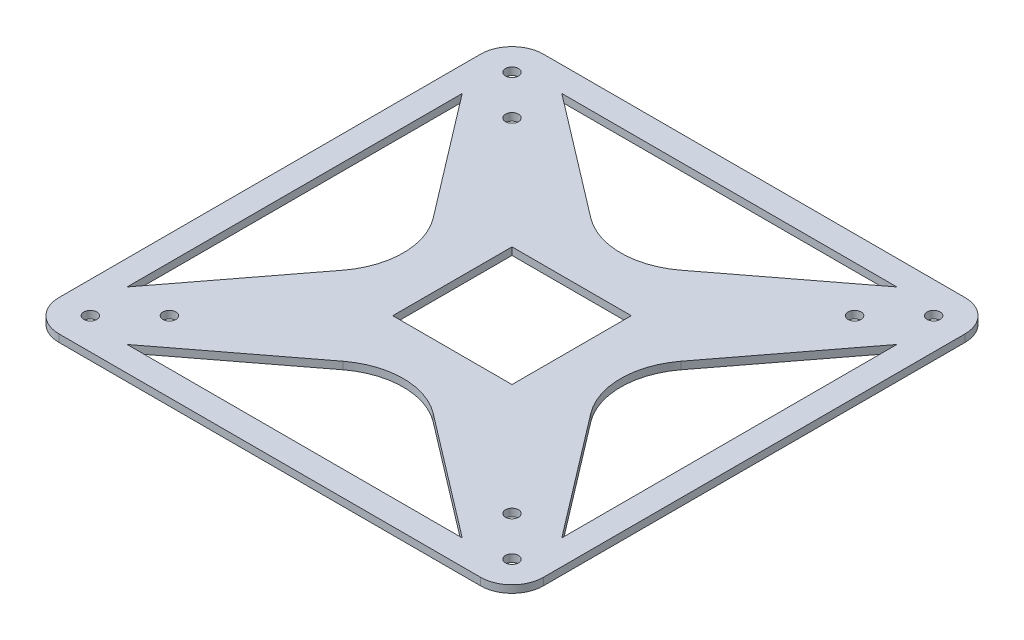
SolidWorks part; units mm, degrees
ref_plane "前视基准面" through (0, 0, 0) normal (0, 0, 1) x (1, 0, 0)
ref_plane "上视基准面" through (0, 0, 0) normal (0, 1, 0) x (1, 0, 0)
ref_plane "右视基准面" through (0, 0, 0) normal (1, 0, 0) x (0, 0, -1)
sketch "草图1" plane through (0, 0, 0) normal (0, 1, 0) x (1, 0, 0)
  line L0 (-12.1309, 33.2719) -> (-44.9616, 58.3185)
  line L5 (-55.3311, 55.3311) -> (-62.9289, 62.9289) construction
  line L6 (33.2719, 12.1309) -> (58.3185, 44.9616)
  line L7 (-33.2719, 12.1309) -> (-58.3185, 44.9616)
  line L8 (12.1309, 33.2719) -> (44.9616, 58.3185)
  line L9 (12.1309, -33.2719) -> (44.9616, -58.3185)
  line L10 (33.2719, -12.1309) -> (58.3185, -44.9616)
  line L11 (-33.2719, -12.1309) -> (-58.3185, -44.9616)
  line L12 (-12.1309, -33.2719) -> (-44.9616, -58.3185)
  line L13 (0, 0) -> (62.5305, 62.5305) construction
  line L14 (-44.9616, 58.3185) -> (44.9616, 58.3185)
  line L15 (-16, -16) -> (16, -16)
  line L16 (-16, -16) -> (-16, 16)
  line L17 (-16, 16) -> (16, 16)
  line L18 (16, -16) -> (16, 16)
  line L19 (-16, -16) -> (16, 16) construction
  line L20 (-16, 16) -> (16, -16) construction
  line L21 (-56.5685, 65) -> (56.5685, 65)
  line L22 (58.3185, 44.9616) -> (58.3185, -44.9616)
  line L23 (65, 56.5685) -> (65, -56.5685)
  line L24 (44.9616, -58.3185) -> (-44.9616, -58.3185)
  line L25 (56.5685, -65) -> (-56.5685, -65)
  line L26 (-58.3185, -44.9616) -> (-58.3185, 44.9616)
  line L27 (-65, -56.5685) -> (-65, 56.5685)
  line L28 (-12.1309, 26.5631) -> (-12.1309, 47.4181) construction
  line L29 (0, 29.1728) -> (0, 24.1728) construction
  circle A0 centre (-56.5685, 56.5685) radius 1.75
  arc A1 (-56.5685, 65) -> (-65, 56.5685) centre (-56.5685, 56.5685) ccw
  circle A2 centre (56.5685, 56.5685) radius 1.75
  arc A3 (65, 56.5685) -> (56.5685, 65) centre (56.5685, 56.5685) ccw
  circle A4 centre (56.5685, -56.5685) radius 1.75
  arc A5 (56.5685, -65) -> (65, -56.5685) centre (56.5685, -56.5685) ccw
  circle A6 centre (-56.5685, -56.5685) radius 1.75
  arc A7 (-65, -56.5685) -> (-56.5685, -65) centre (-56.5685, -56.5685) ccw
  circle A8 centre (45.9619, 45.9619) radius 1.75
  arc A13 (-33.2719, 12.1309) -> (-33.2719, -12.1309) centre (-49.1728, 0) cw
  arc A14 (-12.1309, -33.2719) -> (12.1309, -33.2719) centre (0, -49.1728) cw
  arc A15 (33.2719, -12.1309) -> (33.2719, 12.1309) centre (49.1728, 0) cw
  arc A16 (12.1309, 33.2719) -> (-12.1309, 33.2719) centre (0, 49.1728) cw
  circle A17 centre (45.9619, -45.9619) radius 1.75
  circle A18 centre (-45.9619, -45.9619) radius 1.75
  circle A19 centre (-45.9619, 45.9619) radius 1.75
  point P0 (0, 0)
  point P23 (0, 0)
  point P31 (0, 0)
  point P60 (0, 0)
  point P63 (0, 0)
  dimension "D3" = 3.5
  dimension "D5" = 130
  dimension "D6" = 3.5
  dimension "D7" = 4
  dimension "D8" = 20
  dimension "D1" = 4
  dimension "D2" = 65
  dimension "D4" = 80
  dimension "D9" = 4
  dimension "D10" = 80
  dimension "D11" = 5
  dimension "D12" = 32
extrude "凸台-拉伸1" add sketch "草图1" along normal blind 2
